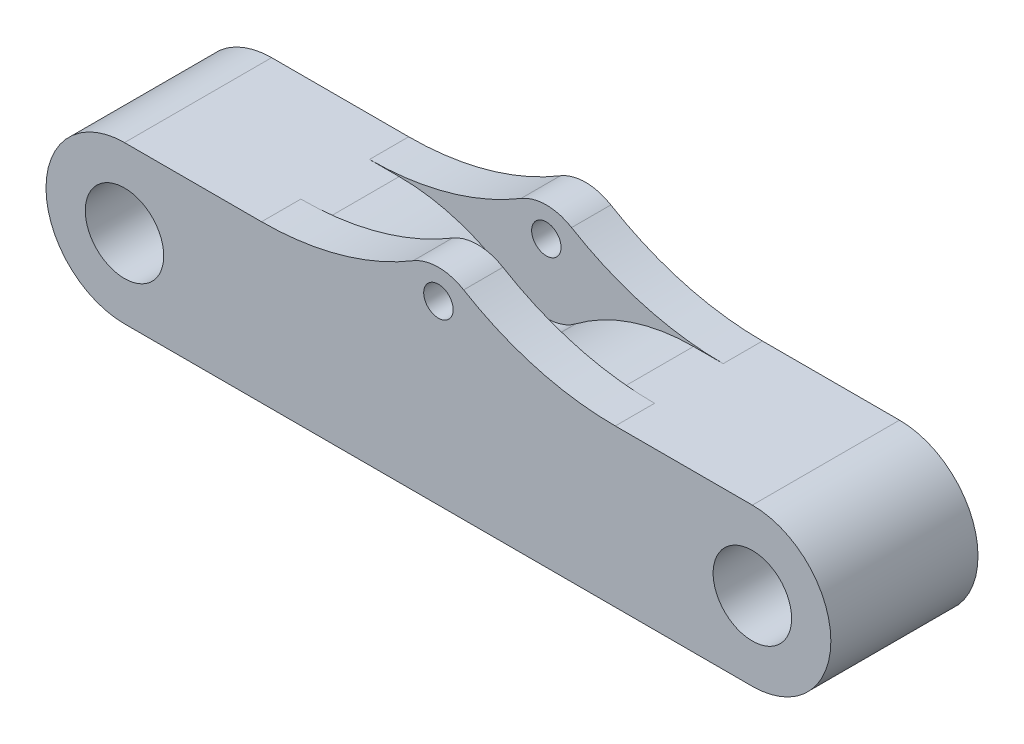
SolidWorks part; units mm, degrees
ref_plane "Front Plane" through (0, 0, 0) normal (0, 0, 1) x (1, 0, 0)
ref_plane "Top Plane" through (0, 0, 0) normal (0, 1, 0) x (1, 0, 0)
ref_plane "Right Plane" through (0, 0, 0) normal (1, 0, 0) x (0, 0, -1)
sketch "Sketch1" plane through (0, 0, 0) normal (0, 0, 1) x (1, 0, 0)
  line L0 (-32, 0) -> (32, 0)
  line L1 (-32, 16) -> (-18.0278, 16)
  line L2 (-32, 8) -> (32, 8) construction
  line L3 (18.0278, 16) -> (32, 16)
  line L4 (-32, 16) -> (32, 16) construction
  line L5 (0, 8) -> (0, 21) construction
  arc A0 (-32, 0) -> (-32, 16) centre (-32, 8) cw
  arc A1 (32, 0) -> (32, 16) centre (32, 8) ccw
  arc A2 (2.5754, 20.2857) -> (-2.5754, 20.2857) centre (0, 16) ccw
  arc A3 (2.5754, 20.2857) -> (18.0278, 16) centre (18.0278, 46) ccw
  arc A4 (-2.5754, 20.2857) -> (-18.0278, 16) centre (-18.0278, 46) cw
  circle A5 centre (0, 18) radius 1.5
  circle A6 centre (-32, 8) radius 4
  circle A7 centre (32, 8) radius 4
  point P4 (0, 0)
  point P14 (5, 16)
  dimension "D2" = 8
  dimension "D3" = 30
  dimension "D1" = 10
  dimension "D4" = 3
  dimension "D6" = 8
  dimension "D7" = 8
  dimension "D5" = 3
extrude "Boss-Extrude1" add sketch "Sketch1" along normal blind 15
sketch "Sketch2" plane through (0, 0, 15) normal (0, 0, 1) x (1, 0, 0)
  line L0 (-18.0278, 16) -> (-15, 16)
  line L1 (18.0278, 16) -> (18.0278, 21)
  line L3 (-18.0278, 21) -> (-18.0278, 16)
  line L4 (15, 16) -> (18.0278, 16)
  line L5 (-18.0278, 21) -> (18.0278, 21)
  arc A0 (-3, 12) -> (3, 12) centre (0, 16) ccw
  arc A1 (-3, 12) -> (-15, 16) centre (-15, -4) ccw
  arc A2 (3, 12) -> (15, 16) centre (15, -4) cw
  dimension "D1" = 20
extrude "Cut-Extrude1" cut sketch "Sketch2" against normal blind 7 from offset 4
